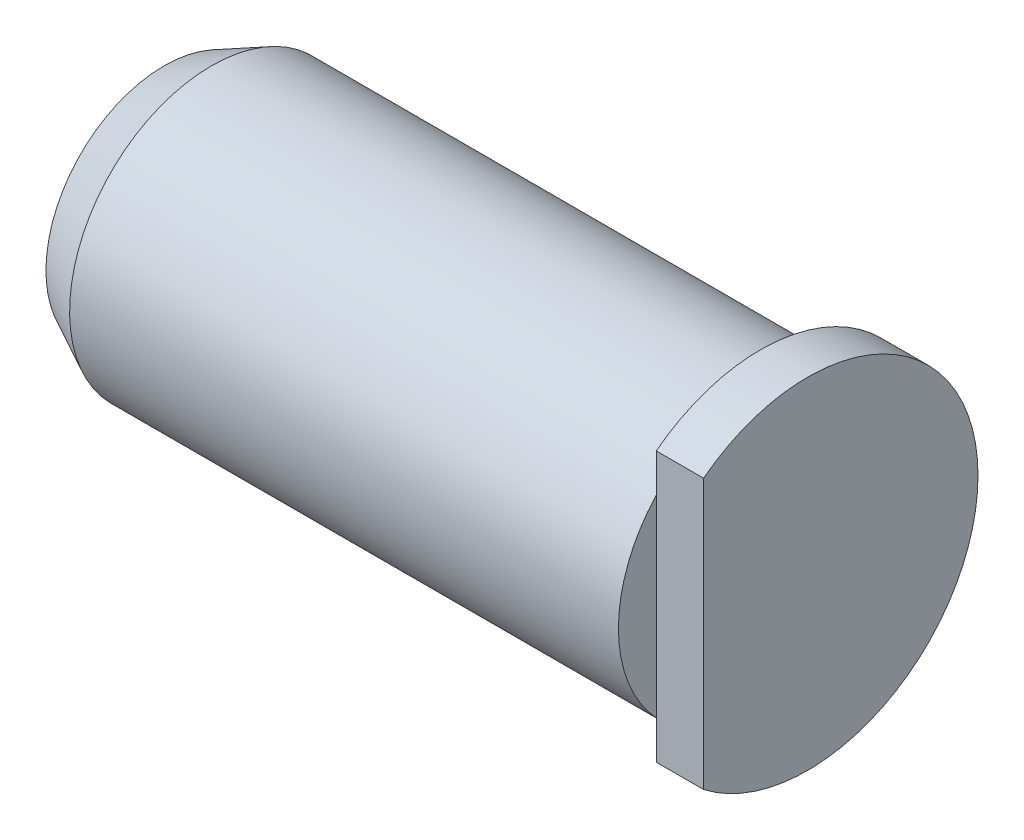
SolidWorks part; units mm, degrees
ref_plane "前视基准面" through (0, 0, 0) normal (0, 0, 1) x (1, 0, 0)
ref_plane "上视基准面" through (0, 0, 0) normal (0, 1, 0) x (1, 0, 0)
ref_plane "右视基准面" through (0, 0, 0) normal (1, 0, 0) x (0, 0, -1)
sketch "草图1" plane through (0, 0, 0) normal (0, 0, 1) x (1, 0, 0)
  line L0 (0, 0) -> (-136, 0)
  line L1 (0, 0) -> (0, 36)
  line L2 (0, 36) -> (-10, 36)
  line L3 (-10, 36) -> (-10, 30)
  line L4 (-10, 30) -> (-126, 30)
  line L5 (-126, 30) -> (-136, 25)
  line L6 (-136, 25) -> (-136, 0)
  dimension "D1" = 36
  dimension "D2" = 136
  dimension "D3" = 116
  dimension "D4" = 30
  dimension "D5" = 10
  dimension "D6" = 25
revolve "旋转1" add sketch "草图1" angle 360 about L0
sketch "草图2" plane through (0, 0, 0) normal (1, 0, 0) x (0, 0, -1)
  line L1 (-22, 36) -> (-36, 36)
  line L2 (-22, 36) -> (-22, -36)
  line L3 (-22, -36) -> (-36, -36)
  line L4 (-36, 36) -> (-36, -36)
  circle A0 centre (0, 0) radius 36 construction
  dimension "D1" = 22
extrude "切除-拉伸1" cut sketch "草图2" against normal blind 10
